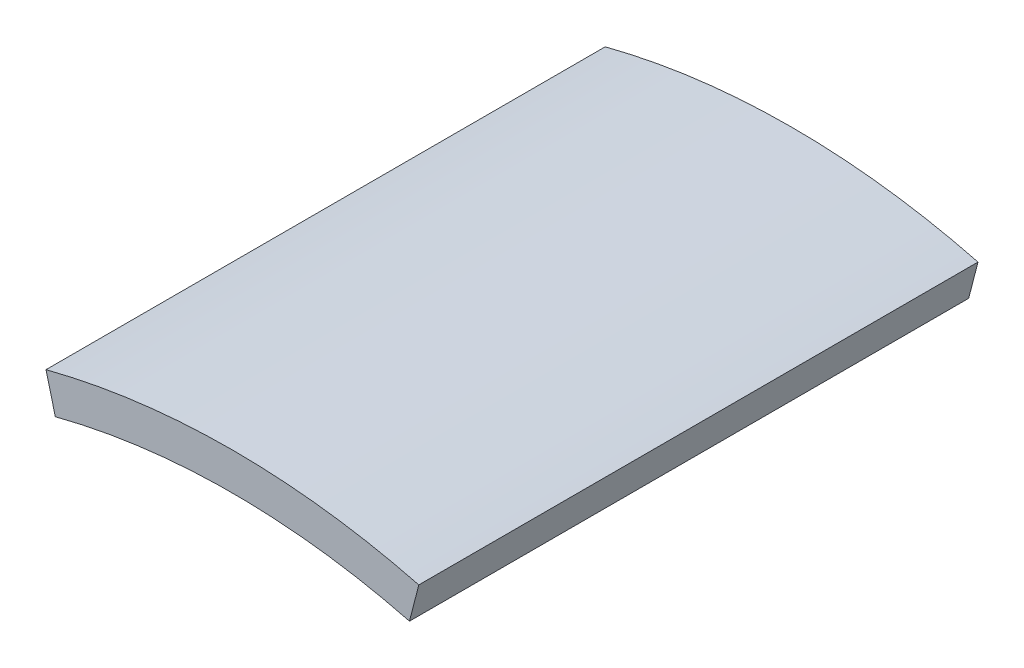
SolidWorks part; units mm, degrees
ref_plane "Plan de face" through (0, 0, 0) normal (0, 0, 1) x (1, 0, 0)
ref_plane "Plan de dessus" through (0, 0, 0) normal (0, 1, 0) x (1, 0, 0)
ref_plane "Plan de droite" through (0, 0, 0) normal (1, 0, 0) x (0, 0, -1)
sketch "Esquisse1" plane through (0, 0, 0) normal (0, 0, 1) x (1, 0, 0)
  line L0 (0, 0) -> (0.5, -1.9365)
  line L1 (20, 0) -> (19.5, -1.9365)
  arc A0 (0, 0) -> (20, 0) centre (10, -38.7298) cw
  arc A1 (0.5, -1.9365) -> (19.5, -1.9365) centre (10, -38.7298) cw
  point P3 (0, 0)
  dimension "D1" = 40
  dimension "D2" = 20
  dimension "D3" = 2
extrude "Boss.-Extru.1" add sketch "Esquisse1" along normal blind 30
